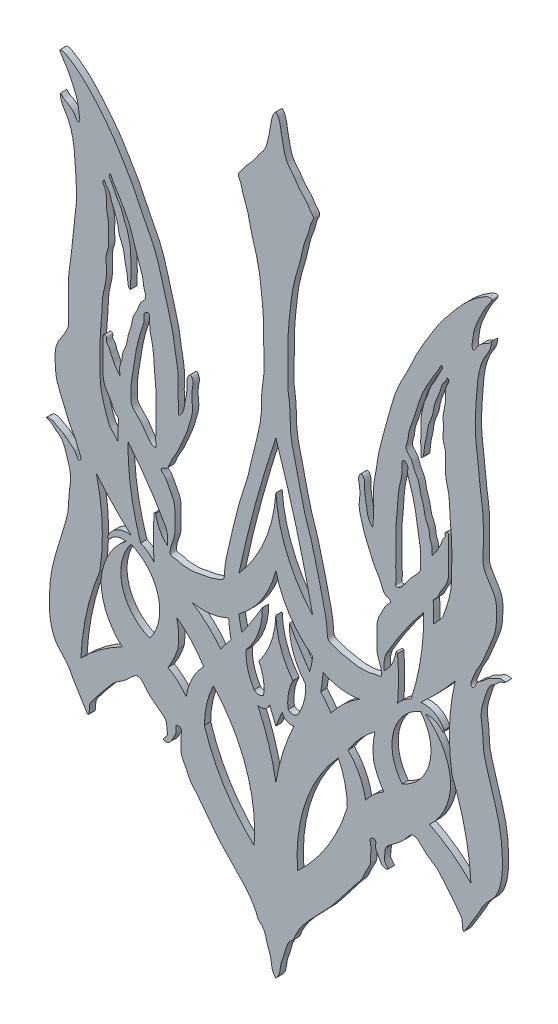
SolidWorks part; units mm, degrees
ref_plane "Спереди" through (0, 0, 0) normal (0, 0, 1) x (1, 0, 0)
ref_plane "Сверху" through (0, 0, 0) normal (0, 1, 0) x (1, 0, 0)
ref_plane "Справа" through (0, 0, 0) normal (1, 0, 0) x (0, 0, -1)
sketch "Эскиз1" plane through (0, 0, 0) normal (0, 0, 1) x (1, 0, 0)
  line L0 (87.6443, -23.7883) -> (87.6443, -6.8916) construction
  line L1 (87.6443, -6.8916) -> (87.6443, 352.3548) construction
  line L3 (87.6443, 68.6318) -> (85.6546, 73.5186)
  line L4 (87.6443, 68.6318) -> (89.6341, 73.5186)
  arc A0 (40.6207, 123.507) -> (44.6469, 97.5316) centre (120.5444, 122.5954) ccw
  arc A1 (40.6207, 123.507) -> (52.5559, 106.1421) centre (-51.0479, 47.7173) cw
  arc A2 (44.6469, 97.5316) -> (48.9353, 94.2011) centre (41.1464, 88.5981) cw
  arc A3 (48.9353, 94.2011) -> (48.9353, 107.9589) centre (131.9116, 101.08) cw
  arc A4 (52.5559, 106.1421) -> (53.1645, 101.095) centre (43.5258, 102.4931) cw
  arc A6 (53.1645, 101.095) -> (49.4634, 108.1691) centre (60.7326, 109.5597) cw
  arc A7 (48.935, 107.9555) -> (49.4634, 108.1691) centre (50.0675, 105.914) cw
  arc A8 (64.6822, 73.5186) -> (59.1188, 62.4923) centre (79.1678, 59.2931) ccw
  arc A9 (59.1188, 62.4923) -> (53.3348, 67.6488) centre (43.2754, 50.5432) ccw
  arc A10 (53.3348, 67.6488) -> (56.4809, 74.2644) centre (31.6379, 82.0231) ccw
  arc A11 (56.4809, 74.2644) -> (56.1084, 82.846) centre (34.8221, 77.623) ccw
  arc A12 (64.6822, 73.5186) -> (56.1084, 82.846) centre (35.8416, 55.6125) ccw
  arc A13 (41.6181, 95.7087) -> (47.5094, 72.7815) centre (35.854, 82.0071) cw
  arc A14 (41.6181, 95.7087) -> (47.5094, 72.7815) centre (53.0477, 86.4251) ccw
  arc A15 (25.6081, 56.3356) -> (38.7862, 66.0056) centre (60.8247, 22.1574) cw
  arc A16 (38.7862, 66.0056) -> (32.0434, 81.1637) centre (52.0503, 80.9846) cw
  arc A17 (40.0148, 95.7087) -> (32.0434, 81.1637) centre (52.4098, 79.4588) ccw
  arc A18 (40.0148, 95.7087) -> (34.589, 93.5264) centre (39.084, 90.1868) ccw
  arc A19 (41.6181, 98.1673) -> (34.1719, 94.2011) centre (40.4092, 91.464) ccw
  arc A20 (30.5806, 109.6374) -> (41.6181, 98.1673) centre (116.5629, 181.3309) ccw
  arc A21 (30.5806, 109.6374) -> (31.6379, 83.1978) centre (-35.2023, 93.7659) cw
  arc A22 (25.6081, 56.3356) -> (31.6379, 83.1978) centre (108.2418, 51.8945) cw
  arc A23 (34.1719, 94.2011) -> (34.589, 93.5264) centre (34.7179, 94.0723) ccw
  arc A24 (72.6436, 90.9214) -> (73.3927, 85.212) centre (115.3568, 93.6216) ccw
  arc A25 (70.0758, 80.9846) -> (73.3927, 85.212) centre (104.2196, 57.6099) cw
  arc A26 (70.0758, 80.9846) -> (60.9509, 89.3983) centre (44.0092, 61.8694) ccw
  arc A27 (60.9509, 89.3983) -> (72.6436, 90.9214) centre (64.518, 107.658) ccw
  arc A28 (80.7379, 32.2385) -> (67.7808, 69.8254) centre (31.257, 36.2081) ccw
  arc A29 (64.9288, 57.4953) -> (67.7808, 69.8254) centre (93.0087, 57.4953) cw
  arc A30 (80.7379, 32.2385) -> (64.9288, 57.4953) centre (119.8675, 74.307) cw
  arc A31 (94.5508, 32.2385) -> (110.3598, 57.4953) centre (55.4212, 74.307) ccw
  arc A32 (110.3598, 57.4953) -> (107.5079, 69.8254) centre (82.28, 57.4953) ccw
  arc A33 (94.5508, 32.2385) -> (107.5079, 69.8254) centre (144.0316, 36.2081) cw
  arc A34 (114.3378, 89.3983) -> (102.6451, 90.9214) centre (110.7707, 107.658) cw
  arc A35 (105.2129, 80.9846) -> (114.3378, 89.3983) centre (131.2795, 61.8694) cw
  arc A36 (105.2129, 80.9846) -> (101.896, 85.212) centre (71.069, 57.6099) ccw
  arc A37 (102.6451, 90.9214) -> (101.896, 85.212) centre (59.9318, 93.6216) cw
  arc A38 (141.1167, 94.2011) -> (140.6996, 93.5264) centre (140.5708, 94.0723) cw
  arc A39 (149.6806, 56.3356) -> (143.6508, 83.1978) centre (67.0469, 51.8945) ccw
  arc A40 (144.708, 109.6374) -> (143.6508, 83.1978) centre (210.491, 93.7659) ccw
  arc A41 (144.708, 109.6374) -> (133.6706, 98.1673) centre (58.7258, 181.3309) cw
  arc A42 (133.6706, 98.1673) -> (141.1167, 94.2011) centre (134.8795, 91.464) cw
  arc A43 (135.2739, 95.7087) -> (140.6996, 93.5264) centre (136.2047, 90.1868) cw
  arc A44 (135.2739, 95.7087) -> (143.2453, 81.1637) centre (122.8789, 79.4588) cw
  arc A45 (136.5025, 66.0056) -> (143.2453, 81.1637) centre (123.2384, 80.9846) ccw
  arc A46 (149.6806, 56.3356) -> (136.5025, 66.0056) centre (114.4639, 22.1574) ccw
  arc A47 (133.6706, 95.7087) -> (127.7793, 72.7815) centre (122.241, 86.4251) cw
  arc A48 (133.6706, 95.7087) -> (127.7793, 72.7815) centre (139.4347, 82.0071) ccw
  arc A49 (110.6065, 73.5186) -> (119.1803, 82.846) centre (139.4471, 55.6125) cw
  arc A50 (118.8077, 74.2644) -> (119.1803, 82.846) centre (140.4665, 77.623) cw
  arc A51 (121.9539, 67.6488) -> (118.8077, 74.2644) centre (143.6508, 82.0231) cw
  arc A52 (116.1699, 62.4923) -> (121.9539, 67.6488) centre (132.0132, 50.5432) cw
  arc A53 (110.6065, 73.5186) -> (116.1699, 62.4923) centre (96.1209, 59.2931) cw
  arc A54 (126.3537, 107.9555) -> (125.8253, 108.1691) centre (125.2211, 105.914) ccw
  arc A55 (122.1242, 101.095) -> (125.8253, 108.1691) centre (114.5561, 109.5597) ccw
  arc A56 (122.7327, 106.1421) -> (122.1242, 101.095) centre (131.7628, 102.4931) ccw
  arc A57 (126.3534, 94.2011) -> (126.3534, 107.9589) centre (43.3771, 101.08) ccw
  arc A58 (130.6418, 97.5316) -> (126.3534, 94.2011) centre (134.1423, 88.5981) ccw
  arc A59 (134.668, 123.507) -> (122.7327, 106.1421) centre (226.3366, 47.7173) ccw
  arc A60 (134.668, 123.507) -> (130.6418, 97.5316) centre (54.7443, 122.5954) cw
  arc A61 (75.9102, 104.8888) -> (87.6443, 132.8603) centre (41.1732, 135.9081) ccw
  arc A62 (75.9102, 104.8888) -> (87.6443, 148.0034) centre (451.7712, 25.7481) cw
  arc A63 (99.3785, 104.8888) -> (87.6443, 132.8603) centre (134.1154, 135.9081) cw
  arc A64 (99.3785, 104.8888) -> (87.6443, 148.0034) centre (-276.4825, 25.7481) ccw
  arc A65 (85.6546, 73.5186) -> (81.8714, 71.5335) centre (82.7705, 74.4176) cw
  arc A66 (87.6443, 53.083) -> (81.8714, 71.5335) centre (17.8027, 41.3588) ccw
  arc A67 (89.6341, 73.5186) -> (93.4173, 71.5335) centre (92.5182, 74.4176) ccw
  arc A68 (87.6443, 53.083) -> (93.4173, 71.5335) centre (157.486, 41.3588) cw
  arc A69 (87.6443, 111.5019) -> (75.9102, 93.6216) centre (57.0652, 118.7792) cw
  arc A70 (75.9102, 93.6216) -> (76.8685, 89.0118) centre (107.3806, 97.7594) ccw
  arc A71 (76.8685, 89.0118) -> (83.3447, 99.1087) centre (-45.6127, 174.6974) ccw
  arc A72 (83.3447, 99.1087) -> (78.1463, 84.8771) centre (62.4821, 98.6641) cw
  arc A73 (80.7379, 75.1856) -> (78.1463, 84.8771) centre (94.8769, 84.1588) cw
  arc A74 (80.7379, 75.1856) -> (83.7649, 75.1856) centre (82.2514, 76.6992) ccw
  arc A75 (83.7649, 75.1856) -> (82.2514, 83.8045) centre (69.0111, 77.037) ccw
  arc A76 (87.6443, 99.1626) -> (82.2514, 83.8045) centre (61.1079, 99.8548) cw
  arc A77 (91.5237, 75.1856) -> (93.0373, 83.8045) centre (106.2776, 77.037) cw
  arc A78 (94.5508, 75.1856) -> (91.5237, 75.1856) centre (93.0373, 76.6992) cw
  arc A79 (94.5508, 75.1856) -> (97.1424, 84.8771) centre (80.4118, 84.1588) ccw
  arc A80 (91.944, 99.1087) -> (97.1424, 84.8771) centre (112.8066, 98.6641) ccw
  arc A81 (98.4202, 89.0118) -> (91.944, 99.1087) centre (220.9014, 174.6974) cw
  arc A82 (99.3785, 93.6216) -> (98.4202, 89.0118) centre (67.908, 97.7594) cw
  arc A83 (87.6443, 111.5019) -> (99.3785, 93.6216) centre (118.2235, 118.7792) ccw
  arc A84 (87.6443, 99.1626) -> (93.0373, 83.8045) centre (114.1808, 99.8548) ccw
  spline S0 degree 3 poles (82.1027, 12.4657) (79.9341, 18.6914) (72.2067, 24.3569) (65.9185, 33.1059) (62.5505, 37.466) (60.1799, 39.943) (59.1555, 43.0897) (57.2647, 45.5543) (57.6286, 48.5225) (57.2368, 50.5201) (57.9183, 52.5735) (56.9495, 53.1909) (55.4861, 53.2614) (56.2486, 51.0634) (55.1896, 49.5498) (54.5036, 47.9051) (53.4075, 46.7279) (51.1035, 46.9894) (53.4402, 48.5489) (52.9045, 50.4248) (53.1315, 52.5819) (50.2686, 54.9996) (47.2077, 56.7477) (43.7411, 62.1873) (40.1307, 57.0478) (36.3563, 55.4003) (34.0123, 52.1175) (31.6232, 49.6208) (29.9193, 47.1505) (28.3136, 45.324) (28.3685, 43.599) (28.0916, 41.1132) (25.4838, 45.8805) (23.6707, 48.1541) (21.3506, 53.1893) (17.5941, 56.1294) (15.6148, 61.936) (15.5097, 68.0525) (15.9741, 74.6221) (17.289, 80.1758) (19.034, 85.376) (20.3139, 90.1381) (21.7721, 94.5747) (21.6409, 98.6721) (22.3333, 102.2806) (22.4635, 106.0403) (21.2552, 109.3896) (20.4336, 112.3281) (19.1765, 114.309) (17.3368, 115.252) (16.6151, 116.5408) (13.9501, 117.1637) (16.6597, 117.6233) (18.0151, 116.3143) (20.2861, 115.5733) (22.0029, 113.6892) (23.906, 112.8857) (24.7011, 110.1686) (25.9462, 111.2271) (24.8035, 113.2315) (24.159, 115.7716) (22.1122, 118.6068) (20.8946, 121.9867) (19.3322, 125.5441) (17.6129, 129.5089) (17.4458, 134.0046) (17.2957, 140.0912) (22.0505, 144.124) (21.6416, 148.9774) (21.7935, 153.6259) (21.4811, 159.1076) (22.6432, 165.8126) (23.1995, 173.1345) (24.6232, 181.9748) (23.765, 191.5281) (23.3918, 198.8905) (20.9362, 204.2846) (19.4503, 205.9635) (18.8575, 209.3893) (19.9586, 207.7428) (21.3919, 207.2624) (22.9247, 206.0347) (23.8774, 204.8209) (24.7322, 203.1653) (25.4143, 204.4362) (24.9731, 205.9617) (24.8711, 208.3515) (23.8043, 211.5847) (22.0026, 215.2682) (20.7759, 217.6358) (18.3336, 220.7887) (20.1657, 220.6691) (22.0637, 219.6809) (26.786, 216.3757) (31.4211, 210.9124) (35.9504, 205.2491) (38.6047, 200.7968) (41.0717, 196.8054) (43.4657, 192.4745) (45.5786, 187.3763) (48.797, 182.0166) (50.8485, 175.8116) (52.3971, 169.5049) (54.0904, 164.0713) (55.1853, 159.4561) (55.6944, 154.6896) (56.8351, 150.296) (56.4354, 145.8923) (56.5698, 142.4952) (56.7674, 140.6512) (56.6429, 138.4535) (58.4364, 140.4087) (58.5125, 143.2164) (59.7639, 147.3027) (59.1349, 150.6113) (60.546, 151.9302) (61.6062, 150.3802) (60.9783, 148.2843) (60.8195, 145.6095) (61.4206, 142.038) (60.3355, 138.7499) (59.3482, 135.2123) (57.8997, 132.2945) (56.5742, 128.4652) (54.2506, 125.5327) (53.3708, 122.086) (51.7176, 121.9147) (50.8205, 120.9474) (52.6711, 119.7166) (53.4663, 117.4305) (55.1877, 114.9802) (55.6358, 111.915) (55.4739, 109.1453) (55.6293, 106.276) (55.2189, 103.833) (54.3757, 101.9514) (54.0729, 100.4765) (53.8467, 98.7589) (56.0297, 98.8443) (57.6189, 98.1528) (59.6896, 98.0729) (61.8788, 98.0468) (64.294, 98.7043) (67.035, 98.9862) (69.132, 99.8917) (71.1395, 100.5472) (71.2883, 102.132) (71.3846, 103.98) (71.6843, 106.4326) (72.3165, 109.0602) (72.9684, 111.8403) (73.7279, 115.3959) (74.8536, 119.4926) (75.763, 123.5727) (76.9652, 127.2471) (78.2259, 131.0447) (79.3431, 135.0503) (80.7614, 142.4724) (83.4282, 150.1397) (82.9512, 158.3066) (84.0107, 163.2854) (83.59, 169.6597) (84.0559, 177.5749) (83.0482, 185.6995) (82.3476, 192.1007) (80.9886, 196.907) (79.5689, 201.5117) (78.8633, 206.1463) (77.0493, 209.8576) (76.689, 212.6324) (75.2575, 214.6117) (76.8358, 216.1245) (77.879, 218.2522) (80.4034, 220.257) (81.8163, 223.0476) (84.1194, 225.3097) (85.0477, 228.2799) (85.6117, 231.0457) (86.1825, 234.1961) (86.3896, 236.5507) (87.6443, 237.7908) knots 0 0 0 0 0.028658 0.043275 0.049534 0.054228 0.058819 0.064724 0.067657 0.072055 0.074743 0.075624 0.077091 0.080033 0.082665 0.085727 0.088171 0.089899 0.093085 0.09504 0.098738 0.10237 0.110881 0.116931 0.12534 0.130966 0.136851 0.143265 0.14693 0.150998 0.153453 0.155706 0.158836 0.169146 0.175056 0.182849 0.190745 0.202253 0.211081 0.2211 0.22852 0.236408 0.243941 0.249861 0.255135 0.260932 0.266943 0.271401 0.275062 0.277427 0.280411 0.282801 0.284651 0.288472 0.292184 0.295167 0.299832 0.302584 0.303471 0.305901 0.311305 0.31655 0.321491 0.327909 0.334558 0.341172 0.348631 0.361775 0.3653 0.370587 0.383408 0.390434 0.401952 0.417351 0.431602 0.445959 0.451733 0.457128 0.459446 0.461227 0.462918 0.467115 0.469213 0.471366 0.472356 0.474352 0.478803 0.483184 0.490226 0.496344 0.499774 0.500928 0.503188 0.510201 0.526825 0.536331 0.543637 0.550744 0.558021 0.566469 0.576206 0.586787 0.596488 0.606229 0.613083 0.618339 0.628411 0.633617 0.638971 0.643137 0.644483 0.645854 0.651354 0.659471 0.66475 0.665493 0.667175 0.670744 0.675956 0.67924 0.687368 0.691401 0.696251 0.702416 0.709709 0.714483 0.715763 0.717201 0.719145 0.723694 0.729034 0.732428 0.737794 0.741861 0.745654 0.749171 0.751124 0.753035 0.755611 0.758771 0.761604 0.764925 0.768896 0.773112 0.777417 0.779908 0.781699 0.784112 0.788713 0.792962 0.796626 0.8019 0.809759 0.816251 0.821199 0.827609 0.834746 0.840382 0.862553 0.871482 0.877812 0.8859 0.90082 0.914379 0.923643 0.930511 0.937411 0.945888 0.95211 0.95598 0.959297 0.961172 0.965011 0.970487 0.975505 0.979301 0.98517 0.98942 0.992411 1 1 1 1
  spline S1 degree 3 poles (82.1027, 12.4657) (84.2993, 11.04) (84.4898, 7.8171) (86.5127, 3.3725) (86.1614, 0.5556) (87.6443, -0.7518) knots 0 0 0 0 0.459955 0.640601 1 1 1 1
  spline S2 degree 3 poles (33.1492, 192.0361) (32.3239, 190.9776) (33.6073, 189.488) (33.8183, 187.2571) (33.5912, 184.1913) (34.768, 180.8287) (34.142, 177.3643) (34.7375, 174.2184) (33.416, 171.4352) (33.916, 167.4649) (33.6419, 163.6672) (32.426, 159.6409) (32.4019, 155.0102) (31.9063, 150.2145) (31.6211, 145.5238) (31.6773, 141.7351) (31.7172, 137.7233) (31.9002, 133.63) (32.978, 129.7883) (33.9667, 126.7415) (34.7739, 124.6373) (35.9477, 123.6027) (36.53, 122.8648) (37.5454, 121.5879) (37.4217, 123.1892) (37.5666, 124.6402) (37.3724, 126.6813) (37.8229, 128.5307) (36.0597, 129.5835) (35.484, 131.9144) (33.8251, 133.8023) (32.9988, 135.8671) (32.5775, 137.8995) (32.7484, 140.1683) (32.6969, 142.6647) (32.7204, 145.3503) (32.6794, 147.1018) (32.7472, 149.4742) (34.0356, 148.8725) (33.4484, 147.6005) (34.7834, 146.6454) (34.9602, 145.1083) (35.8397, 143.8377) (36.3762, 142.2481) (37.3299, 141.4461) (38.2688, 139.6692) (37.6169, 143.0252) (38.8152, 144.4393) (38.7035, 147.2313) (40.2653, 149.5487) (40.4515, 152.7002) (41.8549, 155.6423) (41.9859, 158.862) (43.852, 161.2171) (44.2768, 163.8863) (46.8497, 165.6494) (45.526, 168.176) (45.5393, 170.8684) (44.2898, 173.6945) (43.4083, 176.7928) (42.3605, 179.7494) (41.2587, 183.3179) (39.6884, 186.497) (37.9874, 189.0815) (37.1022, 190.9736) (35.9708, 192.4083) (35.546, 193.416) (34.9644, 194.6072) (34.481, 193.584) (35.0606, 192.9709) (35.4984, 191.9578) (36.1915, 190.5842) (37.1149, 188.6535) (38.6572, 186.6292) (39.1797, 184.1383) (40.3802, 181.9395) (40.9565, 179.5898) (41.4899, 177.0443) (41.4982, 174.3807) (41.5055, 171.851) (41.6679, 169.141) (41.2969, 167.7277) (41.5978, 165.5169) (40.8134, 166.0301) (40.5745, 166.8614) (40.5224, 168.2129) (40.2785, 170.2818) (39.5013, 172.7829) (39.3781, 175.9179) (37.6702, 178.7865) (37.4428, 182.0032) (36.3743, 184.7095) (35.2439, 187.1159) (34.7904, 189.6375) (33.4854, 190.5664) (33.1492, 192.0361) (32.3239, 190.9776) (33.6073, 189.488) knots -0.012612 -0.005761 -0.002075 0 0.007255 0.019718 0.029693 0.047672 0.065407 0.075398 0.089085 0.104151 0.127416 0.139155 0.159578 0.18822 0.203162 0.221786 0.238384 0.256378 0.275818 0.290943 0.298886 0.305592 0.309871 0.315048 0.316266 0.327773 0.336578 0.343481 0.349935 0.360303 0.374097 0.382594 0.389485 0.401439 0.412378 0.423035 0.435398 0.441227 0.444335 0.448491 0.455752 0.462248 0.468297 0.476116 0.48319 0.486816 0.495399 0.506278 0.515895 0.529177 0.542232 0.556628 0.571942 0.583258 0.594987 0.607033 0.616794 0.627412 0.64313 0.656674 0.670279 0.68463 0.706116 0.717022 0.725407 0.734132 0.739585 0.743026 0.745433 0.749878 0.753371 0.760138 0.77021 0.781747 0.793286 0.803307 0.814728 0.82514 0.837744 0.849666 0.859355 0.871506 0.875734 0.877718 0.88086 0.887378 0.895398 0.908474 0.921918 0.936196 0.951395 0.963938 0.974273 0.987388 0.994239 0.997925 1 1.007255 1.019718 1.029693 only from (32.7088, 191.4049) to (32.7088, 191.4049)
  spline S3 degree 3 poles (47.2686, 158.0754) (47.7213, 162.9241) (45.2966, 161.2742) (45.964, 159.5651) (45.3251, 157.6959) (44.4757, 155.1989) (43.5549, 151.8687) (42.7549, 147.538) (42.2447, 143.4146) (41.541, 139.9722) (41.6157, 137.7124) (41.6536, 136.1284) (41.4943, 134.633) (42.3593, 133.2272) (43.8596, 131.8548) (45.2388, 130.3901) (46.1674, 128.8242) (47.1879, 127.4737) (48.047, 126.2665) (49.7786, 126.1221) (49.3203, 127.9742) (49.5218, 129.7723) (49.5314, 132.9689) (49.4172, 136.5451) (49.5613, 140.5116) (49.4214, 144.4013) (48.898, 148.034) (48.8314, 151.5082) (48.2414, 155.3338) (47.2686, 158.0754) (47.7213, 162.9241) (45.2966, 161.2742) knots -0.143996 -0.098331 -0.035995 0 0.019516 0.041316 0.063925 0.095286 0.145724 0.199179 0.268238 0.309127 0.336564 0.356607 0.371756 0.394271 0.417403 0.452475 0.472504 0.488578 0.519641 0.527249 0.545927 0.569891 0.608527 0.666292 0.712585 0.763868 0.81928 0.856004 0.901669 0.964005 1 1.019516 1.041316 1.063925 only from (46.9629, 162.1437) to (46.9629, 162.1437)
  spline S4 degree 3 poles (128.0201, 158.0754) (127.5674, 162.9241) (129.9921, 161.2742) (129.3247, 159.5651) (129.9636, 157.6959) (130.813, 155.1989) (131.7338, 151.8687) (132.5337, 147.538) (133.044, 143.4146) (133.7477, 139.9722) (133.673, 137.7124) (133.6351, 136.1284) (133.7944, 134.633) (132.9293, 133.2272) (131.4291, 131.8548) (130.0499, 130.3901) (129.1213, 128.8242) (128.1008, 127.4737) (127.2417, 126.2665) (125.5101, 126.1221) (125.9684, 127.9742) (125.7669, 129.7723) (125.7573, 132.9689) (125.8715, 136.5451) (125.7274, 140.5116) (125.8672, 144.4013) (126.3907, 148.034) (126.4573, 151.5082) (127.0473, 155.3338) (128.0201, 158.0754) (127.5674, 162.9241) (129.9921, 161.2742) knots -0.143996 -0.098331 -0.035995 0 0.019516 0.041316 0.063925 0.095286 0.145724 0.199179 0.268238 0.309127 0.336564 0.356607 0.371756 0.394271 0.417403 0.452475 0.472504 0.488578 0.519641 0.527249 0.545927 0.569891 0.608527 0.666292 0.712585 0.763868 0.81928 0.856004 0.901669 0.964005 1 1.019516 1.041316 1.063925 only from (128.3258, 162.1437) to (128.3258, 162.1437)
  spline S5 degree 3 poles (142.1395, 192.0361) (142.9648, 190.9776) (141.6814, 189.488) (141.4704, 187.2571) (141.6974, 184.1913) (140.5207, 180.8287) (141.1466, 177.3643) (140.5512, 174.2184) (141.8727, 171.4352) (141.3727, 167.4649) (141.6467, 163.6672) (142.8627, 159.6409) (142.8867, 155.0102) (143.3824, 150.2145) (143.6676, 145.5238) (143.6114, 141.7351) (143.5715, 137.7233) (143.3884, 133.63) (142.3107, 129.7883) (141.322, 126.7415) (140.5148, 124.6373) (139.341, 123.6027) (138.7587, 122.8648) (137.7433, 121.5879) (137.867, 123.1892) (137.7221, 124.6402) (137.9163, 126.6813) (137.4658, 128.5307) (139.229, 129.5835) (139.8047, 131.9144) (141.4636, 133.8023) (142.2899, 135.8671) (142.7112, 137.8995) (142.5403, 140.1683) (142.5918, 142.6647) (142.5683, 145.3503) (142.6093, 147.1018) (142.5414, 149.4742) (141.2531, 148.8725) (141.8402, 147.6005) (140.5053, 146.6454) (140.3285, 145.1083) (139.4489, 143.8377) (138.9125, 142.2481) (137.9587, 141.4461) (137.0198, 139.6692) (137.6717, 143.0252) (136.4735, 144.4393) (136.5852, 147.2313) (135.0234, 149.5487) (134.8372, 152.7002) (133.4338, 155.6423) (133.3028, 158.862) (131.4366, 161.2171) (131.0119, 163.8863) (128.439, 165.6494) (129.7627, 168.176) (129.7494, 170.8684) (130.9989, 173.6945) (131.8804, 176.7928) (132.9282, 179.7494) (134.0299, 183.3179) (135.6003, 186.497) (137.3012, 189.0815) (138.1865, 190.9736) (139.3179, 192.4083) (139.7427, 193.416) (140.3243, 194.6072) (140.8077, 193.584) (140.2281, 192.9709) (139.7902, 191.9578) (139.0971, 190.5842) (138.1737, 188.6535) (136.6315, 186.6292) (136.109, 184.1383) (134.9085, 181.9395) (134.3322, 179.5898) (133.7988, 177.0443) (133.7905, 174.3807) (133.7832, 171.851) (133.6208, 169.141) (133.9918, 167.7277) (133.6909, 165.5169) (134.4753, 166.0301) (134.7142, 166.8614) (134.7663, 168.2129) (135.0101, 170.2818) (135.7874, 172.7829) (135.9106, 175.9179) (137.6185, 178.7865) (137.8459, 182.0032) (138.9144, 184.7095) (140.0448, 187.1159) (140.4983, 189.6375) (141.8033, 190.5664) (142.1395, 192.0361) (142.9648, 190.9776) (141.6814, 189.488) knots -0.012612 -0.005761 -0.002075 0 0.007255 0.019718 0.029693 0.047672 0.065407 0.075398 0.089085 0.104151 0.127416 0.139155 0.159578 0.18822 0.203162 0.221786 0.238384 0.256378 0.275818 0.290943 0.298886 0.305592 0.309871 0.315048 0.316266 0.327773 0.336578 0.343481 0.349935 0.360303 0.374097 0.382594 0.389485 0.401439 0.412378 0.423035 0.435398 0.441227 0.444335 0.448491 0.455752 0.462248 0.468297 0.476116 0.48319 0.486816 0.495399 0.506278 0.515895 0.529177 0.542232 0.556628 0.571942 0.583258 0.594987 0.607033 0.616794 0.627412 0.64313 0.656674 0.670279 0.68463 0.706116 0.717022 0.725407 0.734132 0.739585 0.743026 0.745433 0.749878 0.753371 0.760138 0.77021 0.781747 0.793286 0.803307 0.814728 0.82514 0.837744 0.849666 0.859355 0.871506 0.875734 0.877718 0.88086 0.887378 0.895398 0.908474 0.921918 0.936196 0.951395 0.963938 0.974273 0.987388 0.994239 0.997925 1 1.007255 1.019718 1.029693 only from (142.5799, 191.4049) to (142.5799, 191.4049)
  spline S6 degree 3 poles (93.186, 12.4657) (90.9894, 11.04) (90.7989, 7.8171) (88.776, 3.3725) (89.1273, 0.5556) (87.6443, -0.7518) knots 0 0 0 0 0.459955 0.640601 1 1 1 1
  spline S7 degree 3 poles (93.186, 12.4657) (95.3546, 18.6914) (103.082, 24.3569) (109.3702, 33.1059) (112.7382, 37.466) (115.1088, 39.943) (116.1332, 43.0897) (118.024, 45.5543) (117.6601, 48.5225) (118.0519, 50.5201) (117.3704, 52.5735) (118.3392, 53.1909) (119.8025, 53.2614) (119.0401, 51.0634) (120.0991, 49.5498) (120.7851, 47.9051) (121.8812, 46.7279) (124.1852, 46.9894) (121.8484, 48.5489) (122.3841, 50.4248) (122.1572, 52.5819) (125.02, 54.9996) (128.081, 56.7477) (131.5476, 62.1873) (135.158, 57.0478) (138.9324, 55.4003) (141.2764, 52.1175) (143.6655, 49.6208) (145.3694, 47.1505) (146.9751, 45.324) (146.9202, 43.599) (147.197, 41.1132) (149.8049, 45.8805) (151.618, 48.1541) (153.9381, 53.1893) (157.6945, 56.1294) (159.6739, 61.936) (159.779, 68.0525) (159.3146, 74.6221) (157.9997, 80.1758) (156.2547, 85.376) (154.9747, 90.1381) (153.5166, 94.5747) (153.6478, 98.6721) (152.9553, 102.2806) (152.8252, 106.0403) (154.0334, 109.3896) (154.8551, 112.3281) (156.1122, 114.309) (157.9519, 115.252) (158.6736, 116.5408) (161.3386, 117.1637) (158.629, 117.6233) (157.2736, 116.3143) (155.0026, 115.5733) (153.2858, 113.6892) (151.3827, 112.8857) (150.5876, 110.1686) (149.3425, 111.2271) (150.4852, 113.2315) (151.1297, 115.7716) (153.1765, 118.6068) (154.3941, 121.9867) (155.9564, 125.5441) (157.6757, 129.5089) (157.8429, 134.0046) (157.993, 140.0912) (153.2382, 144.124) (153.6471, 148.9774) (153.4952, 153.6259) (153.8076, 159.1076) (152.6455, 165.8126) (152.0892, 173.1345) (150.6655, 181.9748) (151.5237, 191.5281) (151.8969, 198.8905) (154.3525, 204.2846) (155.8384, 205.9635) (156.4312, 209.3893) (155.33, 207.7428) (153.8968, 207.2624) (152.364, 206.0347) (151.4112, 204.8209) (150.5565, 203.1653) (149.8744, 204.4362) (150.3156, 205.9617) (150.4175, 208.3515) (151.4844, 211.5847) (153.2861, 215.2682) (154.5127, 217.6358) (156.9551, 220.7887) (155.1229, 220.6691) (153.225, 219.6809) (148.5027, 216.3757) (143.8676, 210.9124) (139.3383, 205.2491) (136.684, 200.7968) (134.217, 196.8054) (131.823, 192.4745) (129.7101, 187.3763) (126.4917, 182.0166) (124.4402, 175.8116) (122.8915, 169.5049) (121.1983, 164.0713) (120.1034, 159.4561) (119.5943, 154.6896) (118.4535, 150.296) (118.8533, 145.8923) (118.7188, 142.4952) (118.5213, 140.6512) (118.6458, 138.4535) (116.8523, 140.4087) (116.7762, 143.2164) (115.5248, 147.3027) (116.1538, 150.6113) (114.7427, 151.9302) (113.6825, 150.3802) (114.3104, 148.2843) (114.4692, 145.6095) (113.8681, 142.038) (114.9532, 138.7499) (115.9405, 135.2123) (117.389, 132.2945) (118.7145, 128.4652) (121.0381, 125.5327) (121.9179, 122.086) (123.5711, 121.9147) (124.4682, 120.9474) (122.6176, 119.7166) (121.8223, 117.4305) (120.101, 114.9802) (119.6529, 111.915) (119.8148, 109.1453) (119.6594, 106.276) (120.0698, 103.833) (120.913, 101.9514) (121.2157, 100.4765) (121.442, 98.7589) (119.259, 98.8443) (117.6698, 98.1528) (115.5991, 98.0729) (113.4099, 98.0468) (110.9947, 98.7043) (108.2537, 98.9862) (106.1566, 99.8917) (104.1492, 100.5472) (104.0003, 102.132) (103.9041, 103.98) (103.6044, 106.4326) (102.9722, 109.0602) (102.3203, 111.8403) (101.5608, 115.3959) (100.435, 119.4926) (99.5257, 123.5727) (98.3234, 127.2471) (97.0628, 131.0447) (95.9456, 135.0503) (94.5272, 142.4724) (91.8605, 150.1397) (92.3375, 158.3066) (91.278, 163.2854) (91.6987, 169.6597) (91.2328, 177.5749) (92.2405, 185.6995) (92.9411, 192.1007) (94.3001, 196.907) (95.7197, 201.5117) (96.4254, 206.1463) (98.2393, 209.8576) (98.5997, 212.6324) (100.0312, 214.6117) (98.4528, 216.1245) (97.4097, 218.2522) (94.8853, 220.257) (93.4724, 223.0476) (91.1693, 225.3097) (90.2409, 228.2799) (89.677, 231.0457) (89.1062, 234.1961) (88.8991, 236.5507) (87.6443, 237.7908) knots 0 0 0 0 0.028658 0.043275 0.049534 0.054228 0.058819 0.064724 0.067657 0.072055 0.074743 0.075624 0.077091 0.080033 0.082665 0.085727 0.088171 0.089899 0.093085 0.09504 0.098738 0.10237 0.110881 0.116931 0.12534 0.130966 0.136851 0.143265 0.14693 0.150998 0.153453 0.155706 0.158836 0.169146 0.175056 0.182849 0.190745 0.202253 0.211081 0.2211 0.22852 0.236408 0.243941 0.249861 0.255135 0.260932 0.266943 0.271401 0.275062 0.277427 0.280411 0.282801 0.284651 0.288472 0.292184 0.295167 0.299832 0.302584 0.303471 0.305901 0.311305 0.31655 0.321491 0.327909 0.334558 0.341172 0.348631 0.361775 0.3653 0.370587 0.383408 0.390434 0.401952 0.417351 0.431602 0.445959 0.451733 0.457128 0.459446 0.461227 0.462918 0.467115 0.469213 0.471366 0.472356 0.474352 0.478803 0.483184 0.490226 0.496344 0.499774 0.500928 0.503188 0.510201 0.526825 0.536331 0.543637 0.550744 0.558021 0.566469 0.576206 0.586787 0.596488 0.606229 0.613083 0.618339 0.628411 0.633617 0.638971 0.643137 0.644483 0.645854 0.651354 0.659471 0.66475 0.665493 0.667175 0.670744 0.675956 0.67924 0.687368 0.691401 0.696251 0.702416 0.709709 0.714483 0.715763 0.717201 0.719145 0.723694 0.729034 0.732428 0.737794 0.741861 0.745654 0.749171 0.751124 0.753035 0.755611 0.758771 0.761604 0.764925 0.768896 0.773112 0.777417 0.779908 0.781699 0.784112 0.788713 0.792962 0.796626 0.8019 0.809759 0.816251 0.821199 0.827609 0.834746 0.840382 0.862553 0.871482 0.877812 0.8859 0.90082 0.914379 0.923643 0.930511 0.937411 0.945888 0.95211 0.95598 0.959297 0.961172 0.965011 0.970487 0.975505 0.979301 0.98517 0.98942 0.992411 1 1 1 1
extrude "Бобышка-Вытянуть1" add sketch "Эскиз1" along normal blind 2 contours S6 S7 S0 S1 S5 A59 A60 A58 A57 A54 A55 A56 A39 A46 A45 A44 A43 A38 A42 A41 A40 A31 A33 A32 A28 A30 A29 A26 A27 A24 A25 A19 A23 A18 A17 A16 A15 A22 A21 A20 A7 A3 A2
